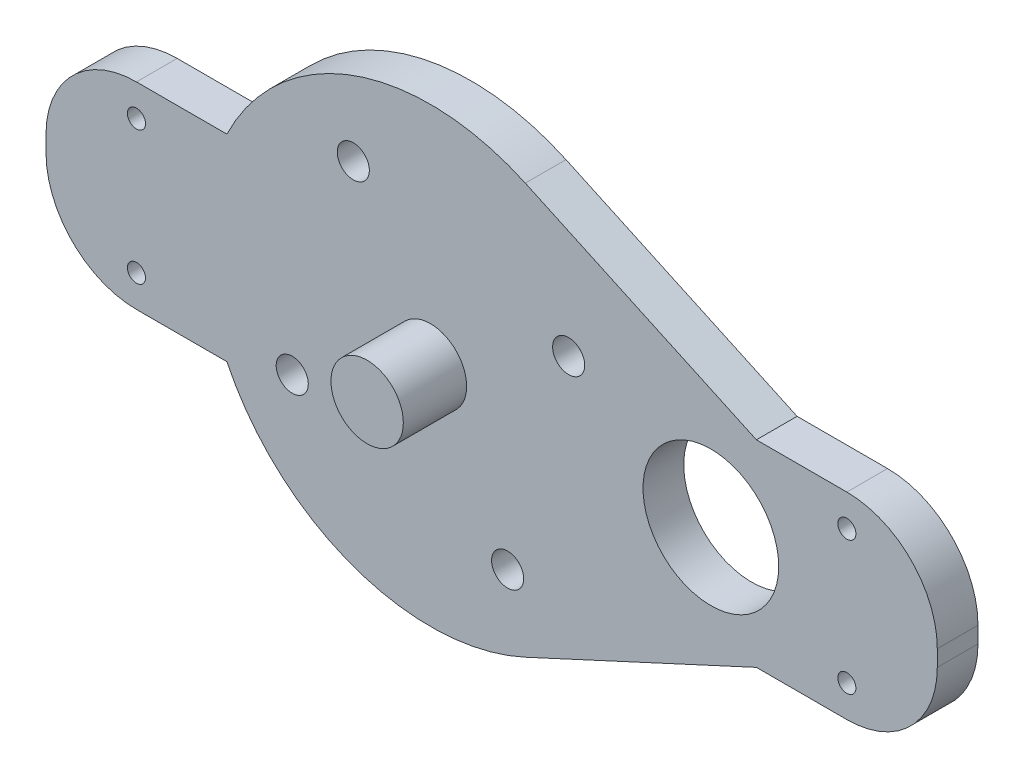
SolidWorks part; units mm, degrees
ref_plane "Front Plane" through (0, 0, 0) normal (0, 0, 1) x (1, 0, 0)
ref_plane "Top Plane" through (0, 0, 0) normal (0, 1, 0) x (1, 0, 0)
ref_plane "Right Plane" through (0, 0, 0) normal (1, 0, 0) x (0, 0, -1)
sketch "Sketch1" plane through (0, 0, 0) normal (0, 0, 1) x (1, 0, 0)
  line L0 (10.4839, 22.6956) -> (36.0323, 10.8939)
  line L1 (36.0323, -10.8939) -> (10.4839, -22.6956)
  circle A0 centre (0, 0) radius 22.215 construction
  circle A1 centre (31, 0) radius 10.2 construction
  arc A2 (10.4839, 22.6956) -> (10.4839, -22.6956) centre (0, 0) ccw
  arc A3 (36.0323, -10.8939) -> (36.0323, 10.8939) centre (31, 0) ccw
  dimension "D1" = 20.4
  dimension "D2" = 44.43
  dimension "D4" = 25
  dimension "D5" = 12
  dimension "D3" = 31
extrude "Boss-Extrude1" add sketch "Sketch1" along normal blind 4.5
sketch "Sketch2" plane through (0, 0, 4.5) normal (0, 0, 1) x (1, 0, 0)
  circle A0 centre (31, 0) radius 7.5
  dimension "D1" = 15
extrude "Cut-Extrude1" cut sketch "Sketch2" against normal through all
sketch "Sketch3" plane through (0, 0, 4.5) normal (0, 0, 1) x (1, 0, 0)
  circle A0 centre (0, 0) radius 4
  dimension "D1" = 8
extrude "Boss-Extrude2" add sketch "Sketch3" along normal blind 7
sketch "Sketch4" plane through (0, 0, 0) normal (0, 0, -1) x (-1, 0, 0)
  line L0 (-36.0323, 10.8939) -> (-56.0323, 10.8939)
  line L1 (-36.0323, -10.8939) -> (-56.0323, -10.8939)
  line L2 (-56.0323, -10.8939) -> (-56.0323, 10.8939)
  line L3 (22.5016, 10.8939) -> (42.5016, 10.8939)
  line L4 (42.5016, 10.8939) -> (42.5016, -10.8939)
  line L5 (42.5016, -10.8939) -> (22.5016, -10.8939)
  arc A0 (-10.4839, -22.6956) -> (-10.4839, 22.6956) centre (0, 0) ccw construction
  arc A1 (22.5016, -10.8939) -> (22.5016, 10.8939) centre (0, 0) ccw
  arc A2 (-36.0323, 10.8939) -> (-36.0323, -10.8939) centre (-31, 0) ccw construction
  arc A3 (-36.0323, 10.8939) -> (-36.0323, -10.8939) centre (-31, 0) ccw
  dimension "D1" = 20
  dimension "D2" = 20
extrude "Boss-Extrude3" add sketch "Sketch4" against normal up to surface (4.5 mm away) up to face at (4, 0, 4.5)
fillet "Fillet1" radius 10 4 edges at (-42.5016, 10.8939, 2.25) (-42.5016, -10.8939, 2.25) (56.0323, -10.8939, 2.25) (56.0323, 10.8939, 2.25)
sketch "Sketch6" plane through (0, 0, 0) normal (0, 0, -1) x (-1, 0, 0)
  line L0 (32.5016, -7.3844) -> (32.5016, 7.3844) construction
  line L2 (42.5016, 0) -> (-56.0323, 0) construction
  line L3 (32.5016, 7.3844) -> (38.7752, 0) construction
  line L4 (38.7752, 0) -> (32.5016, -7.3844) construction
  line L5 (-46.0323, -10.8939) -> (-46.0323, 10.8939) construction
  line L6 (32.5016, -7.3844) -> (-48.7204, -7.3844) construction
  line L7 (32.5016, 7.3844) -> (-48.7204, 7.3844) construction
  line L8 (42.5016, -0.8939) -> (42.5016, 0.8939) construction
  line L9 (-56.0323, 0.8939) -> (-56.0323, -0.8939) construction
  line L10 (41.7762, 16.9611) -> (41.8868, 17.0874) construction
  circle A2 centre (32.5016, -7.3844) radius 1
  circle A3 centre (32.5016, 7.3844) radius 1
  circle A4 centre (-46.0323, -7.3844) radius 1
  circle A5 centre (-46.0323, 7.3844) radius 1
  point P5 (32.5016, 0)
  point P16 (-46.0323, 7.3844)
  point P20 (-46.0323, -7.3844)
  dimension "D1" = 2
extrude "Cut-Extrude2" cut sketch "Sketch6" against normal through all
sketch "Sketch7" plane through (0, 0, 0) normal (0, 0, -1) x (-1, 0, 0)
  line L1 (-46.0408, 9.6361) -> (-47.9865, 8.5028)
  line L2 (-47.9865, 8.5028) -> (-47.978, 6.2512)
  line L3 (-47.978, 6.2512) -> (-46.0237, 5.1328)
  line L4 (-46.0237, 5.1328) -> (-44.078, 6.266)
  line L5 (-44.078, 6.266) -> (-44.0866, 8.5176)
  line L6 (-44.0866, 8.5176) -> (-46.0408, 9.6361)
  line L7 (-46.0408, -5.1328) -> (-47.9865, -6.266)
  line L8 (-47.9865, -6.266) -> (-47.978, -8.5176)
  line L9 (-47.978, -8.5176) -> (-46.0237, -9.6361)
  line L10 (-46.0237, -9.6361) -> (-44.078, -8.5028)
  line L11 (-44.078, -8.5028) -> (-44.0866, -6.2512)
  line L12 (-44.0866, -6.2512) -> (-46.0408, -5.1328)
  line L13 (32.5009, 9.6361) -> (30.5512, 8.5096)
  line L14 (30.5512, 8.5096) -> (30.552, 6.2579)
  line L15 (30.552, 6.2579) -> (32.5024, 5.1327)
  line L16 (32.5024, 5.1327) -> (34.452, 6.2593)
  line L17 (34.452, 6.2593) -> (34.4512, 8.5109)
  line L18 (34.4512, 8.5109) -> (32.5009, 9.6361)
  line L19 (32.5009, -5.1327) -> (30.5512, -6.2593)
  line L20 (30.5512, -6.2593) -> (30.552, -8.5109)
  line L21 (30.552, -8.5109) -> (32.5024, -9.6361)
  line L22 (32.5024, -9.6361) -> (34.452, -8.5096)
  line L23 (34.452, -8.5096) -> (34.4512, -6.2579)
  line L24 (34.4512, -6.2579) -> (32.5009, -5.1327)
  circle A0 centre (-46.0323, 7.3844) radius 1.95 construction
  circle A1 centre (-46.0323, -7.3844) radius 1.95 construction
  circle A2 centre (32.5016, 7.3844) radius 1.95 construction
  circle A3 centre (32.5016, -7.3844) radius 1.95 construction
  dimension "D1" = 2.2517
extrude "Cut-Extrude3" cut sketch "Sketch7" against normal blind 3
ref_plane "Plane1" through (28.1083, 5.3152, -2) normal (-0.3601, 0.9329, 0) x (0.9329, 0.3601, 0)
sketch "Sketch10" plane through (0, 0, 4.5) normal (0, 0, 1) x (1, 0, 0)
  circle A0 centre (0, 0) radius 17.5 construction
  circle A1 centre (8.5306, -15.28) radius 1
  circle A2 centre (-15.28, -8.5306) radius 1
  circle A3 centre (-8.5306, 15.28) radius 1
  circle A4 centre (15.28, 8.5306) radius 1
  point P14 (0, 0)
  dimension "D1" = 35
  dimension "D2" = 2
  dimension "D3" = 4
extrude "Cut-Extrude4" cut sketch "Sketch10" against normal through all
sketch "Sketch11" plane through (0, 0, 4.5) normal (0, 0, 1) x (1, 0, 0)
  circle A0 centre (-8.5306, 15.28) radius 1.775
  circle A1 centre (15.28, 8.5306) radius 1.775
  circle A2 centre (8.5306, -15.28) radius 1.775
  circle A3 centre (-15.28, -8.5306) radius 1.775
  dimension "3.55" = 3.55
extrude "Cut-Extrude5" cut sketch "Sketch11" against normal blind 2.5
